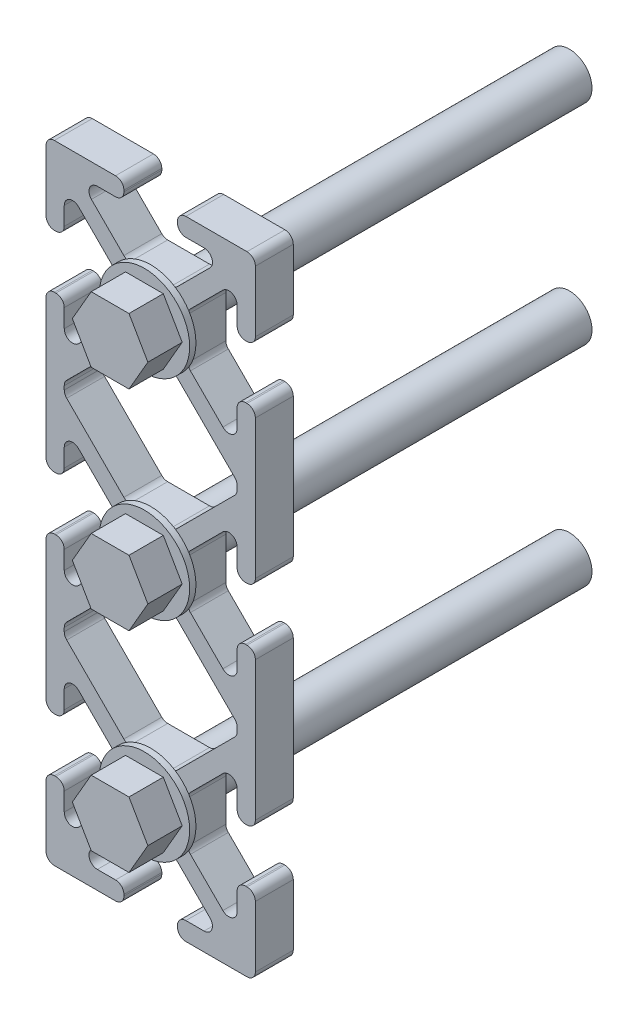
SolidWorks part; units mm, degrees
ref_plane "Front Plane" through (0, 0, 0) normal (0, 0, 1) x (1, 0, 0)
ref_plane "Top Plane" through (0, 0, 0) normal (0, 1, 0) x (1, 0, 0)
ref_plane "Right Plane" through (0, 0, 0) normal (1, 0, 0) x (0, 0, -1)
sketch "Sketch1" plane through (0, 0, 0) normal (0, 0, 1) x (1, 0, 0)
  line L0 (-12.7, 38.1) -> (-12.7, 12.7) construction
  line L1 (-12.7, -38.1) -> (12.7, -38.1) construction
  line L2 (-12.7, 12.7) -> (-12.7, -12.7) construction
  line L3 (-12.7, 38.1) -> (12.7, 38.1) construction
  line L4 (-12.7, -12.7) -> (-12.7, -38.1) construction
  line L5 (-12.7, -38.1) -> (12.7, 38.1) construction
  line L6 (-12.7, 38.1) -> (12.7, -38.1) construction
  line L7 (12.7, 38.1) -> (12.7, 12.7) construction
  line L8 (12.7, 12.7) -> (12.7, -12.7) construction
  line L9 (12.7, -12.7) -> (12.7, -38.1) construction
  line L10 (-12.7, 12.7) -> (12.7, 12.7) construction
  line L11 (-12.7, -12.7) -> (12.7, -12.7) construction
  line L12 (12.7, -12.7) -> (-12.7, -38.1) construction
  line L13 (12.7, -38.1) -> (-12.7, -12.7) construction
  line L14 (0, 38.1) -> (0, -38.1) construction
  line L15 (12.7, 12.7) -> (-12.7, 38.1) construction
  line L16 (12.7, 38.1) -> (-12.7, 12.7) construction
  line L17 (-12.7, 37.084) -> (-12.7, 29.6672)
  line L18 (-11.684, 28.6512) -> (-11.5062, 28.6512)
  line L19 (-10.4902, 29.6672) -> (-10.4902, 31.8748)
  line L20 (-8.7558, 32.5932) -> (-4.8188, 28.6562)
  line L21 (-4.5212, 27.9378) -> (-4.5212, 22.8622)
  line L22 (-4.8188, 22.1438) -> (-8.7558, 18.2068)
  line L23 (-10.4902, 18.9252) -> (-10.4902, 21.1328)
  line L24 (-11.5062, 22.1488) -> (-11.684, 22.1488)
  line L25 (-12.7, 21.1328) -> (-12.7, 4.2672)
  line L26 (-12.7, 0) -> (12.7, 0) construction
  line L27 (-12.7, -25.4) -> (12.7, -25.4) construction
  line L28 (-12.7, 25.4) -> (12.7, 25.4) construction
  line L29 (4.2672, 38.1) -> (11.684, 38.1)
  line L30 (3.2512, 36.9062) -> (3.2512, 37.084)
  line L31 (6.4748, 35.8902) -> (4.2672, 35.8902)
  line L32 (3.2562, 30.2188) -> (7.1932, 34.1558)
  line L33 (-2.5378, 29.9212) -> (2.5378, 29.9212)
  line L34 (-7.1932, 34.1558) -> (-3.2562, 30.2188)
  line L35 (-4.2672, 35.8902) -> (-6.4748, 35.8902)
  line L36 (-3.2512, 37.084) -> (-3.2512, 36.9062)
  line L37 (-11.684, 38.1) -> (-4.2672, 38.1)
  line L38 (4.5212, 2.5378) -> (4.5212, -2.5378)
  line L39 (11.5062, 22.1488) -> (11.684, 22.1488)
  line L40 (10.4902, 18.9252) -> (10.4902, 21.1328)
  line L41 (4.8188, 22.1438) -> (8.7558, 18.2068)
  line L42 (4.5212, 27.9378) -> (4.5212, 22.8622)
  line L43 (8.7558, 32.5932) -> (4.8188, 28.6562)
  line L44 (10.4902, 29.6672) -> (10.4902, 31.8748)
  line L45 (11.684, 28.6512) -> (11.5062, 28.6512)
  line L46 (12.7, 37.084) -> (12.7, 29.6672)
  line L47 (-10.4902, 12.4736) -> (-10.4902, 12.9264)
  line L48 (-10.1926, 13.6448) -> (-3.2562, 20.5812)
  line L49 (-2.5378, 20.8788) -> (2.5378, 20.8788)
  line L50 (10.4902, 12.4736) -> (10.4902, 12.9264)
  line L51 (10.1926, 13.6448) -> (3.2562, 20.5812)
  line L52 (10.1926, 11.7552) -> (3.2562, 4.8188)
  line L53 (-2.5378, 4.5212) -> (2.5378, 4.5212)
  line L54 (-10.1926, 11.7552) -> (-3.2562, 4.8188)
  line L55 (-2.5378, -4.5212) -> (2.5378, -4.5212)
  line L56 (-10.1926, -11.7552) -> (-3.2562, -4.8188)
  line L57 (10.1926, -11.7552) -> (3.2562, -4.8188)
  line L58 (10.4902, -12.4736) -> (10.4902, -12.9264)
  line L59 (10.1926, -13.6448) -> (3.2562, -20.5812)
  line L60 (-2.5378, -20.8788) -> (2.5378, -20.8788)
  line L61 (-10.1926, -13.6448) -> (-3.2562, -20.5812)
  line L62 (-10.4902, -12.4736) -> (-10.4902, -12.9264)
  line L63 (4.8188, -3.2562) -> (8.7558, -7.1932)
  line L64 (11.5062, -22.1488) -> (11.684, -22.1488)
  line L65 (10.4902, -18.9252) -> (10.4902, -21.1328)
  line L66 (4.8188, -22.1438) -> (8.7558, -18.2068)
  line L67 (4.5212, -27.9378) -> (4.5212, -22.8622)
  line L68 (8.7558, -32.5932) -> (4.8188, -28.6562)
  line L69 (10.4902, -29.6672) -> (10.4902, -31.8748)
  line L70 (11.684, -28.6512) -> (11.5062, -28.6512)
  line L71 (12.7, -37.084) -> (12.7, -29.6672)
  line L72 (3.2512, -36.9062) -> (3.2512, -37.084)
  line L73 (6.4748, -35.8902) -> (4.2672, -35.8902)
  line L74 (3.2562, -30.2188) -> (7.1932, -34.1558)
  line L75 (-2.5378, -29.9212) -> (2.5378, -29.9212)
  line L76 (-7.1932, -34.1558) -> (-3.2562, -30.2188)
  line L77 (-4.2672, -35.8902) -> (-6.4748, -35.8902)
  line L78 (-3.2512, -37.084) -> (-3.2512, -36.9062)
  line L79 (-11.684, -38.1) -> (-4.2672, -38.1)
  line L80 (4.2672, -38.1) -> (11.684, -38.1)
  line L81 (4.8188, 3.2562) -> (8.7558, 7.1932)
  line L82 (-11.5062, -22.1488) -> (-11.684, -22.1488)
  line L83 (-10.4902, -18.9252) -> (-10.4902, -21.1328)
  line L84 (-4.8188, -22.1438) -> (-8.7558, -18.2068)
  line L85 (-4.5212, -27.9378) -> (-4.5212, -22.8622)
  line L86 (-8.7558, -32.5932) -> (-4.8188, -28.6562)
  line L87 (-10.4902, -29.6672) -> (-10.4902, -31.8748)
  line L88 (-11.684, -28.6512) -> (-11.5062, -28.6512)
  line L89 (-12.7, -37.084) -> (-12.7, -29.6672)
  line L90 (-4.8188, 3.2562) -> (-8.7558, 7.1932)
  line L91 (-10.4902, 6.4748) -> (-10.4902, 4.2672)
  line L92 (-11.5062, 3.2512) -> (-11.684, 3.2512)
  line L93 (-4.5212, 2.5378) -> (-4.5212, -2.5378)
  line L94 (-12.7, -21.1328) -> (-12.7, -4.2672)
  line L95 (-4.8188, -3.2562) -> (-8.7558, -7.1932)
  line L96 (-10.4902, -6.4748) -> (-10.4902, -4.2672)
  line L97 (-11.5062, -3.2512) -> (-11.684, -3.2512)
  line L98 (10.4902, -6.4748) -> (10.4902, -4.2672)
  line L99 (10.4902, 6.4748) -> (10.4902, 4.2672)
  line L100 (11.5062, 3.2512) -> (11.684, 3.2512)
  line L101 (11.5062, -3.2512) -> (11.684, -3.2512)
  line L102 (12.7, -21.1328) -> (12.7, -4.2672)
  line L103 (12.7, 21.1328) -> (12.7, 4.2672)
  circle A0 centre (0, 25.4) radius 2.6035
  circle A1 centre (0, 0) radius 2.6035
  circle A2 centre (0, -25.4) radius 2.6035
  arc A3 (-12.7, 21.1328) -> (-11.684, 22.1488) centre (-11.684, 21.1328) cw
  arc A4 (-11.5062, 22.1488) -> (-10.4902, 21.1328) centre (-11.5062, 21.1328) cw
  arc A5 (-10.4902, 18.9252) -> (-8.7558, 18.2068) centre (-9.4742, 18.9252) ccw
  arc A6 (-4.8188, 22.1438) -> (-4.5212, 22.8622) centre (-5.5372, 22.8622) ccw
  arc A7 (-4.5212, 27.9378) -> (-4.8188, 28.6562) centre (-5.5372, 27.9378) ccw
  arc A8 (-8.7558, 32.5932) -> (-10.4902, 31.8748) centre (-9.4742, 31.8748) ccw
  arc A9 (-10.4902, 29.6672) -> (-11.5062, 28.6512) centre (-11.5062, 29.6672) cw
  arc A10 (-11.684, 28.6512) -> (-12.7, 29.6672) centre (-11.684, 29.6672) cw
  arc A11 (4.2672, 38.1) -> (3.2512, 37.084) centre (4.2672, 37.084) ccw
  arc A12 (3.2512, 36.9062) -> (4.2672, 35.8902) centre (4.2672, 36.9062) ccw
  arc A13 (6.4748, 35.8902) -> (7.1932, 34.1558) centre (6.4748, 34.8742) cw
  arc A14 (3.2562, 30.2188) -> (2.5378, 29.9212) centre (2.5378, 30.9372) cw
  arc A15 (-2.5378, 29.9212) -> (-3.2562, 30.2188) centre (-2.5378, 30.9372) cw
  arc A16 (-7.1932, 34.1558) -> (-6.4748, 35.8902) centre (-6.4748, 34.8742) cw
  arc A17 (-4.2672, 35.8902) -> (-3.2512, 36.9062) centre (-4.2672, 36.9062) ccw
  arc A18 (-3.2512, 37.084) -> (-4.2672, 38.1) centre (-4.2672, 37.084) ccw
  arc A19 (12.7, 21.1328) -> (11.684, 22.1488) centre (11.684, 21.1328) ccw
  arc A20 (11.5062, 22.1488) -> (10.4902, 21.1328) centre (11.5062, 21.1328) ccw
  arc A21 (10.4902, 18.9252) -> (8.7558, 18.2068) centre (9.4742, 18.9252) cw
  arc A22 (4.8188, 22.1438) -> (4.5212, 22.8622) centre (5.5372, 22.8622) cw
  arc A23 (4.5212, 27.9378) -> (4.8188, 28.6562) centre (5.5372, 27.9378) cw
  arc A24 (8.7558, 32.5932) -> (10.4902, 31.8748) centre (9.4742, 31.8748) cw
  arc A25 (10.4902, 29.6672) -> (11.5062, 28.6512) centre (11.5062, 29.6672) ccw
  arc A26 (11.684, 28.6512) -> (12.7, 29.6672) centre (11.684, 29.6672) ccw
  arc A27 (12.7, 37.084) -> (11.684, 38.1) centre (11.684, 37.084) ccw
  arc A28 (-11.684, 38.1) -> (-12.7, 37.084) centre (-11.684, 37.084) ccw
  arc A29 (-10.1926, 13.6448) -> (-10.4902, 12.9264) centre (-9.4742, 12.9264) ccw
  arc A30 (-2.5378, 20.8788) -> (-3.2562, 20.5812) centre (-2.5378, 19.8628) ccw
  arc A31 (10.1926, 13.6448) -> (10.4902, 12.9264) centre (9.4742, 12.9264) cw
  arc A32 (2.5378, 20.8788) -> (3.2562, 20.5812) centre (2.5378, 19.8628) cw
  arc A33 (10.1926, 11.7552) -> (10.4902, 12.4736) centre (9.4742, 12.4736) ccw
  arc A34 (2.5378, 4.5212) -> (3.2562, 4.8188) centre (2.5378, 5.5372) ccw
  arc A35 (-2.5378, 4.5212) -> (-3.2562, 4.8188) centre (-2.5378, 5.5372) cw
  arc A36 (-10.1926, 11.7552) -> (-10.4902, 12.4736) centre (-9.4742, 12.4736) cw
  arc A37 (2.5378, -4.5212) -> (3.2562, -4.8188) centre (2.5378, -5.5372) cw
  arc A38 (-2.5378, -4.5212) -> (-3.2562, -4.8188) centre (-2.5378, -5.5372) ccw
  arc A39 (10.1926, -11.7552) -> (10.4902, -12.4736) centre (9.4742, -12.4736) cw
  arc A40 (10.1926, -13.6448) -> (10.4902, -12.9264) centre (9.4742, -12.9264) ccw
  arc A41 (2.5378, -20.8788) -> (3.2562, -20.5812) centre (2.5378, -19.8628) ccw
  arc A42 (-2.5378, -20.8788) -> (-3.2562, -20.5812) centre (-2.5378, -19.8628) cw
  arc A43 (-10.1926, -13.6448) -> (-10.4902, -12.9264) centre (-9.4742, -12.9264) cw
  arc A44 (-10.1926, -11.7552) -> (-10.4902, -12.4736) centre (-9.4742, -12.4736) ccw
  arc A45 (12.7, -21.1328) -> (11.684, -22.1488) centre (11.684, -21.1328) cw
  arc A46 (11.5062, -22.1488) -> (10.4902, -21.1328) centre (11.5062, -21.1328) cw
  arc A47 (10.4902, -18.9252) -> (8.7558, -18.2068) centre (9.4742, -18.9252) ccw
  arc A48 (4.8188, -22.1438) -> (4.5212, -22.8622) centre (5.5372, -22.8622) ccw
  arc A49 (4.5212, -27.9378) -> (4.8188, -28.6562) centre (5.5372, -27.9378) ccw
  arc A50 (8.7558, -32.5932) -> (10.4902, -31.8748) centre (9.4742, -31.8748) ccw
  arc A51 (10.4902, -29.6672) -> (11.5062, -28.6512) centre (11.5062, -29.6672) cw
  arc A52 (11.684, -28.6512) -> (12.7, -29.6672) centre (11.684, -29.6672) cw
  arc A53 (4.2672, -38.1) -> (3.2512, -37.084) centre (4.2672, -37.084) cw
  arc A54 (3.2512, -36.9062) -> (4.2672, -35.8902) centre (4.2672, -36.9062) cw
  arc A55 (6.4748, -35.8902) -> (7.1932, -34.1558) centre (6.4748, -34.8742) ccw
  arc A56 (3.2562, -30.2188) -> (2.5378, -29.9212) centre (2.5378, -30.9372) ccw
  arc A57 (-2.5378, -29.9212) -> (-3.2562, -30.2188) centre (-2.5378, -30.9372) ccw
  arc A58 (-7.1932, -34.1558) -> (-6.4748, -35.8902) centre (-6.4748, -34.8742) ccw
  arc A59 (-4.2672, -35.8902) -> (-3.2512, -36.9062) centre (-4.2672, -36.9062) cw
  arc A60 (-3.2512, -37.084) -> (-4.2672, -38.1) centre (-4.2672, -37.084) cw
  arc A61 (12.7, -37.084) -> (11.684, -38.1) centre (11.684, -37.084) cw
  arc A62 (-12.7, -21.1328) -> (-11.684, -22.1488) centre (-11.684, -21.1328) ccw
  arc A63 (-11.5062, -22.1488) -> (-10.4902, -21.1328) centre (-11.5062, -21.1328) ccw
  arc A64 (-10.4902, -18.9252) -> (-8.7558, -18.2068) centre (-9.4742, -18.9252) cw
  arc A65 (-4.8188, -22.1438) -> (-4.5212, -22.8622) centre (-5.5372, -22.8622) cw
  arc A66 (-4.5212, -27.9378) -> (-4.8188, -28.6562) centre (-5.5372, -27.9378) cw
  arc A67 (-8.7558, -32.5932) -> (-10.4902, -31.8748) centre (-9.4742, -31.8748) cw
  arc A68 (-10.4902, -29.6672) -> (-11.5062, -28.6512) centre (-11.5062, -29.6672) ccw
  arc A69 (-11.684, -28.6512) -> (-12.7, -29.6672) centre (-11.684, -29.6672) ccw
  arc A70 (-11.684, -38.1) -> (-12.7, -37.084) centre (-11.684, -37.084) cw
  arc A71 (-4.8188, 3.2562) -> (-4.5212, 2.5378) centre (-5.5372, 2.5378) cw
  arc A72 (-10.4902, 6.4748) -> (-8.7558, 7.1932) centre (-9.4742, 6.4748) cw
  arc A73 (-11.5062, 3.2512) -> (-10.4902, 4.2672) centre (-11.5062, 4.2672) ccw
  arc A74 (-12.7, 4.2672) -> (-11.684, 3.2512) centre (-11.684, 4.2672) ccw
  arc A75 (-4.8188, -3.2562) -> (-4.5212, -2.5378) centre (-5.5372, -2.5378) ccw
  arc A76 (-10.4902, -6.4748) -> (-8.7558, -7.1932) centre (-9.4742, -6.4748) ccw
  arc A77 (-11.5062, -3.2512) -> (-10.4902, -4.2672) centre (-11.5062, -4.2672) cw
  arc A78 (-12.7, -4.2672) -> (-11.684, -3.2512) centre (-11.684, -4.2672) cw
  arc A79 (4.8188, 3.2562) -> (4.5212, 2.5378) centre (5.5372, 2.5378) ccw
  arc A80 (4.8188, -3.2562) -> (4.5212, -2.5378) centre (5.5372, -2.5378) cw
  arc A81 (10.4902, 6.4748) -> (8.7558, 7.1932) centre (9.4742, 6.4748) ccw
  arc A82 (10.4902, -6.4748) -> (8.7558, -7.1932) centre (9.4742, -6.4748) cw
  arc A83 (11.5062, -3.2512) -> (10.4902, -4.2672) centre (11.5062, -4.2672) ccw
  arc A84 (11.5062, 3.2512) -> (10.4902, 4.2672) centre (11.5062, 4.2672) cw
  arc A85 (12.7, -4.2672) -> (11.684, -3.2512) centre (11.684, -4.2672) ccw
  arc A86 (12.7, 4.2672) -> (11.684, 3.2512) centre (11.684, 4.2672) cw
  point P0 (0, 0)
  point P26 (-12.7, 22.1488)
  point P41 (-12.7, 28.6512)
  point P107 (-6.7244, 17.113)
  point P120 (0, 20.8788)
  point P121 (10.4902, 12.7)
  point P132 (-10.4902, 12.7)
  point P249 (-4.5212, 0)
  dimension "D2" = 5.207
  dimension "D8" = 1.016
  dimension "D9" = 3.2512
  dimension "D10" = 1.1049
  dimension "D1" = 25.4
  dimension "D3" = 2.2098
  dimension "D4" = 6.5024
  dimension "D5" = 4.5212
  dimension "D6" = 1.1049
  dimension "D7" = 1.1049
  dimension "D11" = 4.5212
extrude "Main Extrusion" add sketch "Sketch1" along normal mid plane 4.5974
sketch "Sketch2" plane through (0, 0, 2.2987) normal (0, 0, 1) x (1, 0, 0)
  line L0 (-4.2672, 38.1) -> (-11.684, 38.1) construction
  line L1 (-12.7, -38.1) -> (12.7, -38.1) construction
  line L2 (-12.7, 38.1) -> (-12.7, 12.7) construction
  line L3 (-12.7, 38.1) -> (12.7, 38.1) construction
  line L4 (-12.7, 21.1328) -> (-12.7, 4.2672) construction
  line L5 (-12.7, -38.1) -> (12.7, 38.1) construction
  line L6 (-12.7, 38.1) -> (12.7, -38.1) construction
  line L7 (-12.7, 12.7) -> (-12.7, -12.7) construction
  line L8 (0, 38.1) -> (0, -38.1) construction
  line L9 (-12.7, -4.2672) -> (-12.7, -21.1328) construction
  line L10 (-12.7, -12.7) -> (-12.7, -38.1) construction
  line L11 (12.7, 38.1) -> (12.7, 12.7) construction
  line L12 (12.7, 4.2672) -> (12.7, 21.1328) construction
  line L13 (12.7, 12.7) -> (12.7, -12.7) construction
  line L14 (12.7, -21.1328) -> (12.7, -4.2672) construction
  line L15 (12.7, -12.7) -> (12.7, -38.1) construction
  line L16 (-12.7, 25.4) -> (12.7, 25.4) construction
  line L17 (-12.7, 0) -> (12.7, 0) construction
  line L18 (-12.7, -25.4) -> (12.7, -25.4) construction
  line L19 (-12.7, 12.7) -> (12.7, 12.7) construction
  line L20 (-12.7, -12.7) -> (12.7, -12.7) construction
  line L21 (-3.2512, 36.9062) -> (-3.2512, 37.084) construction
  line L22 (-10.4902, 38.1) -> (-9.4742, 38.1)
  line L23 (-6.477, 38.1) -> (-5.461, 38.1)
  line L24 (-12.7, 38.1) -> (12.7, 12.7) construction
  line L25 (12.7, 12.7) -> (-12.7, -12.7) construction
  line L26 (-12.7, -12.7) -> (12.7, -38.1) construction
  line L27 (-12.7, -38.1) -> (12.7, -12.7) construction
  line L28 (12.7, -12.7) -> (-12.7, 12.7) construction
  line L29 (-12.7, 12.7) -> (12.7, 38.1) construction
  line L30 (6.477, 38.1) -> (5.461, 38.1)
  line L31 (10.4902, 38.1) -> (9.4742, 38.1)
  line L32 (-12.7, 14.9098) -> (-12.7, 15.9258)
  line L33 (-12.7, 18.923) -> (-12.7, 19.939)
  line L34 (-12.7, 31.877) -> (-12.7, 30.861)
  line L35 (-12.7, 35.8902) -> (-12.7, 34.8742)
  line L36 (12.7, 35.8902) -> (12.7, 34.8742)
  line L37 (12.7, 31.877) -> (12.7, 30.861)
  line L38 (12.7, 18.923) -> (12.7, 19.939)
  line L39 (12.7, 14.9098) -> (12.7, 15.9258)
  line L40 (12.7, 10.4902) -> (12.7, 9.4742)
  line L41 (12.7, 6.477) -> (12.7, 5.461)
  line L42 (-12.7, 10.4902) -> (-12.7, 9.4742)
  line L43 (-12.7, 6.477) -> (-12.7, 5.461)
  line L44 (12.7, -6.477) -> (12.7, -5.461)
  line L45 (12.7, -10.4902) -> (12.7, -9.4742)
  line L46 (12.7, -14.9098) -> (12.7, -15.9258)
  line L47 (12.7, -18.923) -> (12.7, -19.939)
  line L48 (12.7, -31.877) -> (12.7, -30.861)
  line L49 (12.7, -35.8902) -> (12.7, -34.8742)
  line L50 (10.4902, -38.1) -> (9.4742, -38.1)
  line L51 (6.477, -38.1) -> (5.461, -38.1)
  line L52 (-6.477, -38.1) -> (-5.461, -38.1)
  line L53 (-10.4902, -38.1) -> (-9.4742, -38.1)
  line L54 (-12.7, -35.8902) -> (-12.7, -34.8742)
  line L55 (-12.7, -31.877) -> (-12.7, -30.861)
  line L56 (-12.7, -18.923) -> (-12.7, -19.939)
  line L57 (-12.7, -14.9098) -> (-12.7, -15.9258)
  line L58 (-12.7, -10.4902) -> (-12.7, -9.4742)
  line L59 (-12.7, -6.477) -> (-12.7, -5.461)
  arc A0 (-10.4902, 38.1) -> (-9.4742, 38.1) centre (-9.9822, 38.1) ccw
  arc A1 (-6.477, 38.1) -> (-5.461, 38.1) centre (-5.969, 38.1) ccw
  arc A2 (6.477, 38.1) -> (5.461, 38.1) centre (5.969, 38.1) cw
  arc A3 (10.4902, 38.1) -> (9.4742, 38.1) centre (9.9822, 38.1) cw
  arc A4 (-12.7, 14.9098) -> (-12.7, 15.9258) centre (-12.7, 15.4178) ccw
  arc A5 (-12.7, 18.923) -> (-12.7, 19.939) centre (-12.7, 19.431) ccw
  arc A6 (-12.7, 31.877) -> (-12.7, 30.861) centre (-12.7, 31.369) cw
  arc A7 (-12.7, 35.8902) -> (-12.7, 34.8742) centre (-12.7, 35.3822) cw
  arc A8 (12.7, 35.8902) -> (12.7, 34.8742) centre (12.7, 35.3822) ccw
  arc A9 (12.7, 31.877) -> (12.7, 30.861) centre (12.7, 31.369) ccw
  arc A10 (12.7, 18.923) -> (12.7, 19.939) centre (12.7, 19.431) cw
  arc A11 (12.7, 14.9098) -> (12.7, 15.9258) centre (12.7, 15.4178) cw
  arc A12 (12.7, 10.4902) -> (12.7, 9.4742) centre (12.7, 9.9822) ccw
  arc A13 (12.7, 6.477) -> (12.7, 5.461) centre (12.7, 5.969) ccw
  arc A14 (-12.7, 10.4902) -> (-12.7, 9.4742) centre (-12.7, 9.9822) cw
  arc A15 (-12.7, 6.477) -> (-12.7, 5.461) centre (-12.7, 5.969) cw
  arc A16 (12.7, -6.477) -> (12.7, -5.461) centre (12.7, -5.969) cw
  arc A17 (12.7, -10.4902) -> (12.7, -9.4742) centre (12.7, -9.9822) cw
  arc A18 (12.7, -14.9098) -> (12.7, -15.9258) centre (12.7, -15.4178) ccw
  arc A19 (12.7, -18.923) -> (12.7, -19.939) centre (12.7, -19.431) ccw
  arc A20 (12.7, -31.877) -> (12.7, -30.861) centre (12.7, -31.369) cw
  arc A21 (12.7, -35.8902) -> (12.7, -34.8742) centre (12.7, -35.3822) cw
  arc A22 (10.4902, -38.1) -> (9.4742, -38.1) centre (9.9822, -38.1) ccw
  arc A23 (6.477, -38.1) -> (5.461, -38.1) centre (5.969, -38.1) ccw
  arc A24 (-6.477, -38.1) -> (-5.461, -38.1) centre (-5.969, -38.1) cw
  arc A25 (-10.4902, -38.1) -> (-9.4742, -38.1) centre (-9.9822, -38.1) cw
  arc A26 (-12.7, -35.8902) -> (-12.7, -34.8742) centre (-12.7, -35.3822) ccw
  arc A27 (-12.7, -31.877) -> (-12.7, -30.861) centre (-12.7, -31.369) ccw
  arc A28 (-12.7, -18.923) -> (-12.7, -19.939) centre (-12.7, -19.431) cw
  arc A29 (-12.7, -14.9098) -> (-12.7, -15.9258) centre (-12.7, -15.4178) cw
  arc A30 (-12.7, -10.4902) -> (-12.7, -9.4742) centre (-12.7, -9.9822) ccw
  arc A31 (-12.7, -6.477) -> (-12.7, -5.461) centre (-12.7, -5.969) ccw
  point P0 (0, 0)
  dimension "D1" = 0.508
  dimension "D2" = 2.2098
  dimension "D3" = 2.2098
sketch "Sketch3" plane through (0, 0, 2.2987) normal (0, 0, 1) x (1, 0, 0)
  circle A0 centre (0, 25.4) radius 5.4864
  circle A1 centre (0, 0) radius 5.4864
  circle A2 centre (0, -25.4) radius 5.4864
  dimension "D1" = 10.9728
extrude "Boss-Extrude1" add sketch "Sketch3" along normal blind 0.762
sketch "Sketch4" plane through (0, 0, 3.0607) normal (0, 0, 1) x (1, 0, 0)
  line L1 (4.5827, 0) -> (2.2914, 3.9687)
  line L2 (2.2914, 3.9687) -> (-2.2914, 3.9687)
  line L3 (-2.2914, 3.9687) -> (-4.5827, 0)
  line L4 (-4.5827, 0) -> (-2.2914, -3.9688)
  line L5 (-2.2914, -3.9688) -> (2.2914, -3.9688)
  line L6 (2.2914, -3.9688) -> (4.5827, 0)
  line L7 (4.5827, 25.4) -> (2.2914, 29.3688)
  line L8 (2.2914, 29.3688) -> (-2.2914, 29.3688)
  line L9 (-2.2914, 29.3688) -> (-4.5827, 25.4)
  line L10 (-4.5827, 25.4) -> (-2.2914, 21.4313)
  line L11 (-2.2914, 21.4313) -> (2.2914, 21.4313)
  line L12 (2.2914, 21.4313) -> (4.5827, 25.4)
  line L13 (4.5827, -25.4) -> (2.2914, -21.4312)
  line L14 (2.2914, -21.4312) -> (-2.2914, -21.4312)
  line L15 (-2.2914, -21.4312) -> (-4.5827, -25.4)
  line L16 (-4.5827, -25.4) -> (-2.2914, -29.3687)
  line L17 (-2.2914, -29.3687) -> (2.2914, -29.3687)
  line L18 (2.2914, -29.3687) -> (4.5827, -25.4)
  circle A0 centre (0, 0) radius 3.9688 construction
  circle A1 centre (0, 25.4) radius 3.9687 construction
  circle A2 centre (0, -25.4) radius 3.9687 construction
  dimension "D1" = 7.9375
extrude "Boss-Extrude2" add sketch "Sketch4" along normal blind 4.1656
sketch "Sketch5" plane through (0, 0, 2.2987) normal (0, 0, -1) x (-1, 0, 0)
  circle A0 centre (0, 0) radius 2.7432
  circle A1 centre (0, 25.4) radius 2.7432
  circle A2 centre (0, -25.4) radius 2.7432
  dimension "D1" = 5.4864
extrude "Boss-Extrude3" add sketch "Sketch5" along normal blind 50.8
